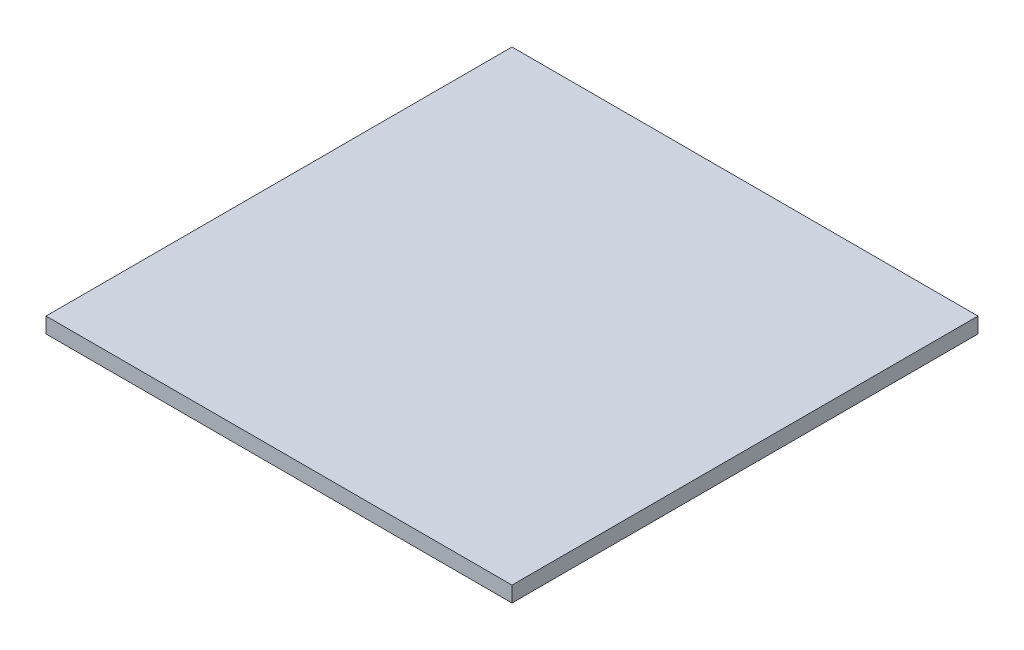
SolidWorks part; units mm, degrees
ref_plane "前视基准面" through (0, 0, 0) normal (0, 0, 1) x (1, 0, 0)
ref_plane "上视基准面" through (0, 0, 0) normal (0, 1, 0) x (1, 0, 0)
ref_plane "右视基准面" through (0, 0, 0) normal (1, 0, 0) x (0, 0, -1)
other "Configuration Table"
sketch "草图1" plane through (0, 0, 0) normal (0, 1, 0) x (1, 0, 0)
  line L1 (-150, -150) -> (150, -150)
  line L2 (-150, -150) -> (-150, 150)
  line L3 (-150, 150) -> (150, 150)
  line L4 (150, -150) -> (150, 150)
  line L5 (-150, -150) -> (150, 150) construction
  line L6 (-150, 150) -> (150, -150) construction
  point P0 (0, 0)
  dimension "D1" = 300
  dimension "D2" = 300
extrude "凸台-拉伸1" add sketch "草图1" along normal blind 10
